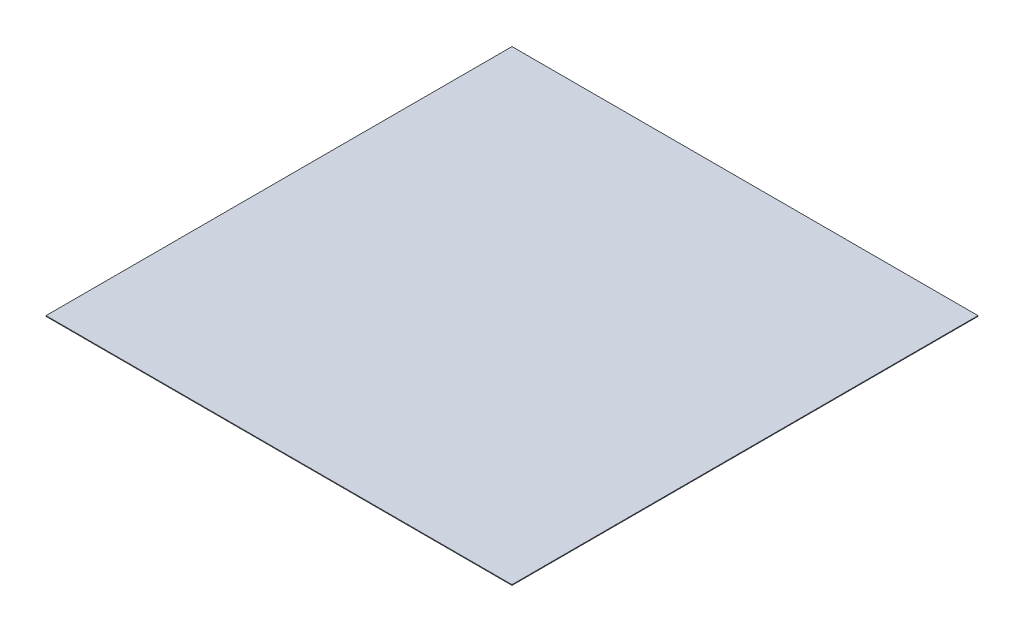
SolidWorks part; units mm, degrees
ref_plane "Front Plane" through (0, 0, 0) normal (0, 0, 1) x (1, 0, 0)
ref_plane "Top Plane" through (0, 0, 0) normal (0, 1, 0) x (1, 0, 0)
ref_plane "Right Plane" through (0, 0, 0) normal (1, 0, 0) x (0, 0, -1)
sketch "Sketch1" plane through (0, 0, 0) normal (0, 1, 0) x (1, 0, 0)
  line L1 (1700, -1700) -> (-1700, -1700)
  line L2 (1700, -1700) -> (1700, 1700)
  line L3 (1700, 1700) -> (-1700, 1700)
  line L4 (-1700, -1700) -> (-1700, 1700)
  line L5 (1700, -1700) -> (-1700, 1700) construction
  line L6 (1700, 1700) -> (-1700, -1700) construction
  point P0 (0, 0)
  dimension "D1" = 3400
  dimension "D2" = 3400
extrude "Boss-Extrude1" add sketch "Sketch1" along normal blind 5
